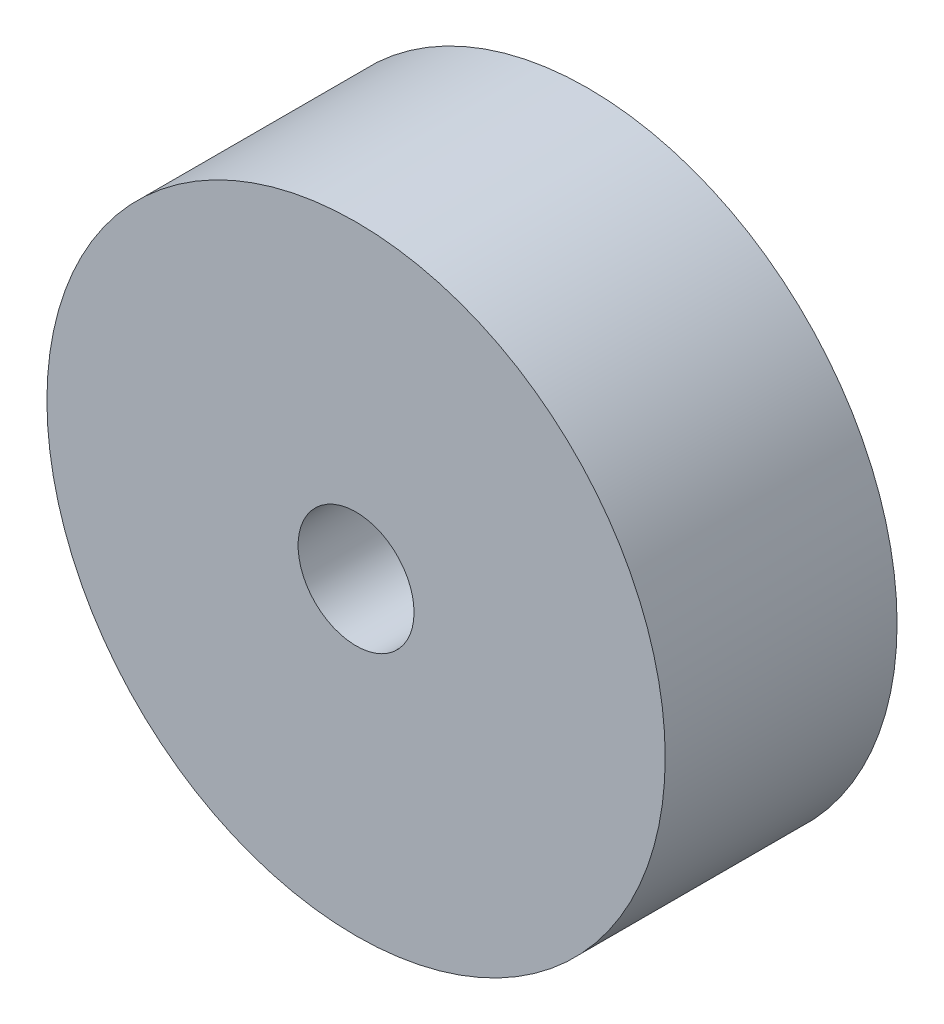
SolidWorks part; units mm, degrees
ref_plane "Front Plane" through (0, 0, 0) normal (0, 0, 1) x (1, 0, 0)
ref_plane "Top Plane" through (0, 0, 0) normal (0, 1, 0) x (1, 0, 0)
ref_plane "Right Plane" through (0, 0, 0) normal (1, 0, 0) x (0, 0, -1)
sketch "Sketch3" plane through (0, 0, 0) normal (0, 0, 1) x (1, 0, 0)
  circle A0 centre (0, 0) radius 101.6
  dimension "D1" = 203.2
extrude "Boss-Extrude2" add sketch "Sketch3" along normal blind 76.2
sketch "Sketch4" plane through (0, 0, 76.2) normal (0, 0, 1) x (1, 0, 0)
  circle A0 centre (0, 0) radius 19.05
  dimension "D1" = 38.1
extrude "Cut-Extrude2" cut sketch "Sketch4" against normal blind 76.2
